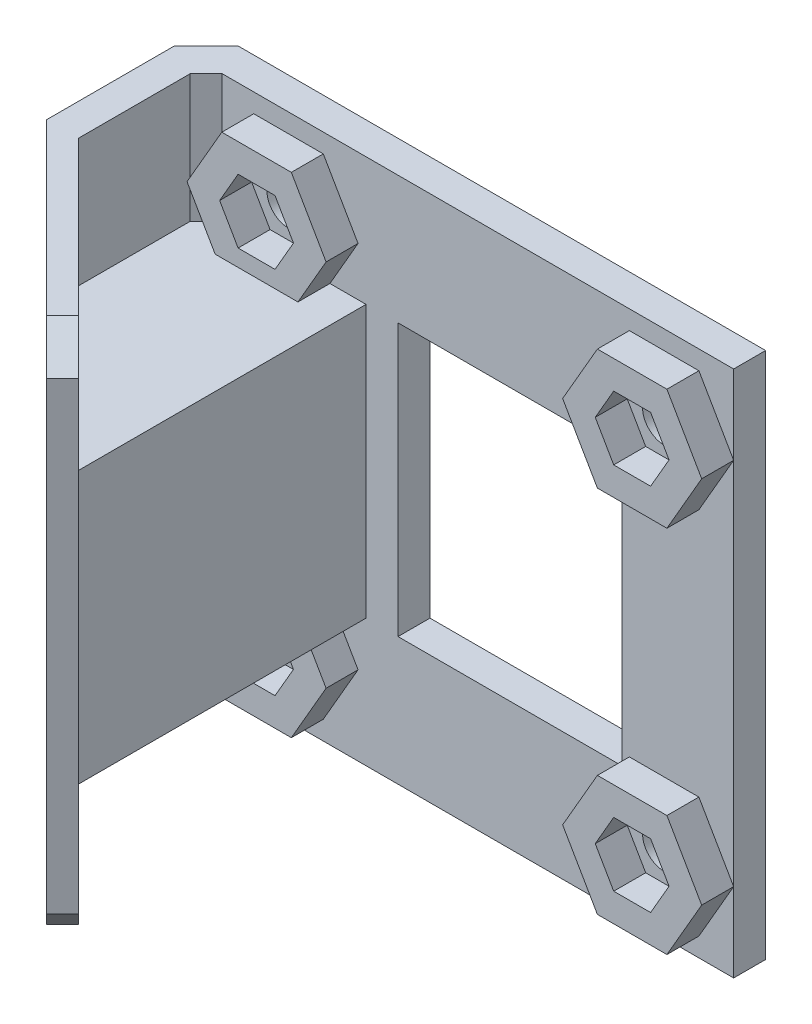
SolidWorks part; units mm, degrees
ref_plane "Front Plane" through (0, 0, 0) normal (0, 0, 1) x (1, 0, 0)
ref_plane "Top Plane" through (0, 0, 0) normal (0, 1, 0) x (1, 0, 0)
ref_plane "Right Plane" through (0, 0, 0) normal (1, 0, 0) x (0, 0, -1)
sketch "Sketch1" plane through (0, 0, 0) normal (0, 0, 1) x (1, 0, 0)
  line L1 (16.5, -16.5) -> (-16.5, -16.5)
  line L2 (16.5, -16.5) -> (16.5, 16.5)
  line L3 (16.5, 16.5) -> (-16.5, 16.5)
  line L4 (-16.5, -16.5) -> (-16.5, 16.5)
  line L5 (16.5, -16.5) -> (-16.5, 16.5) construction
  line L6 (16.5, 16.5) -> (-16.5, -16.5) construction
  circle A0 centre (-11.35, 11.55) radius 1.35
  circle A1 centre (12.15, 11.55) radius 1.35
  circle A2 centre (-11.35, -11.55) radius 1.35
  circle A3 centre (12.15, -11.55) radius 1.35
  point P0 (0, 0)
  point P9 (0, 0)
  dimension "D4" = 2.7
  dimension "D5" = 23.1
  dimension "D6" = 23.1
  dimension "D7" = 4.95
  dimension "D8" = 4.95
  dimension "D10" = 23.5
  dimension "D11" = 5.15
  dimension "D12" = 5.15
  dimension "D1" = 33
  dimension "D2" = 33
  dimension "D3" = 23.5
extrude "Boss-Extrude1" add sketch "Sketch1" along normal blind 2
sketch "Sketch4" plane through (-16.5, 0, 0) normal (-1, 0, 0) x (0, 0, 1)
  line L0 (2, -16.5) -> (0, -16.5) construction
  line L1 (0, 16.5) -> (10, 16.5)
  line L2 (0, 16.5) -> (0, -16.5)
  line L3 (0, -16.5) -> (10, -16.5)
  line L4 (10, 16.5) -> (10, -16.5)
  dimension "D1" = 10
extrude "Boss-Extrude3" add sketch "Sketch4" along normal blind 2
sketch "Sketch5" plane through (0, -16.5, 0) normal (0, -1, 0) x (1, 0, 0)
  line L0 (-18.5, 10) -> (-6.4792, 22.0208)
  line L1 (-6.4792, 22.0208) -> (-5.4792, 21.0208)
  line L2 (-5.4792, 21.0208) -> (-16.5, 10)
  line L3 (-16.5, 2) -> (-16.5, 10) construction
  line L4 (-16.5, 10) -> (-18.5, 10)
  dimension "D1" = 135
  dimension "D2" = 17
extrude "Boss-Extrude4" add sketch "Sketch5" against normal up to surface (33 mm away) up to face at (-6.1667, 16.5, 4)
sketch "Sketch6" plane through (-13.25, 0, 13.25) normal (0.7071, 0, -0.7071) x (-0.7071, 0, -0.7071)
  line L0 (-10.9896, 16.5) -> (-10.9896, -16.5) construction
  line L1 (-10.9896, 16.5) -> (4.5962, 16.5) construction
  line L2 (4.5962, -16.5) -> (-10.9896, -16.5) construction
  circle A0 centre (-5.9896, 13.5) radius 1.65
  circle A1 centre (-5.9896, -13.5) radius 1.65
  dimension "D1" = 3.3
  dimension "D2" = 5
  dimension "D3" = 3
  dimension "D4" = 5
  dimension "D5" = 3
  dimension "D6" = 3.3
extrude "Cut-Extrude1" cut sketch "Sketch6" against normal blind 2
chamfer "Chamfer1" distance 1 angle 45 1 edges at (-16.5, 0, 2)
sketch "Sketch7" plane through (0, 0, 2) normal (0, 0, 1) x (1, 0, 0)
  line L1 (-15.5, -7.5) -> (-7.5, -7.5)
  line L2 (-15.5, -7.5) -> (-15.5, 7.5)
  line L3 (-15.5, 7.5) -> (-7.5, 7.5)
  line L4 (-7.5, -7.5) -> (-7.5, 7.5)
  line L5 (-15.5, -7.5) -> (-7.5, 7.5) construction
  line L6 (-15.5, 7.5) -> (-7.5, -7.5) construction
  line L12 (0, 0) -> (-17.9167, 0) construction
  line L15 (-18.5, 16.5) -> (-18.5, -16.5) construction
  point P0 (-11.5, 0)
  point P5 (-11.5, 0)
  dimension "D1" = 3
  dimension "D2" = 15
  dimension "D4" = 8
extrude "Cut-Extrude3" cut sketch "Sketch7" against normal up to surface (2 mm away) and the other way up to surface up to face at (13.5, -11.55, 0) other way up to face at (-8.848, 13.5, 19.652)
sketch "Sketch9" plane through (0, 0, 0) normal (0, 0, -1) x (-1, 0, 0)
  line L1 (6.5, -8.5) -> (18.5, -8.5)
  line L2 (6.5, -8.5) -> (6.5, 8.5)
  line L3 (6.5, 8.5) -> (18.5, 8.5)
  line L4 (18.5, -8.5) -> (18.5, 8.5)
  line L8 (7.5, -7.5) -> (15.5, -7.5) construction
  line L9 (15.5, 7.5) -> (7.5, 7.5) construction
  line L10 (7.5, 7.5) -> (7.5, -7.5) construction
  line L11 (7.5, -7.5) -> (15.5, -7.5)
  line L12 (7.5, -7.5) -> (7.5, 7.5)
  line L13 (7.5, 7.5) -> (15.5, 7.5)
  line L14 (15.5, -7.5) -> (15.5, 7.5)
  line L15 (7.5, -7.5) -> (15.5, 7.5) construction
  line L16 (7.5, 7.5) -> (15.5, -7.5) construction
  line L17 (18.5, 16.5) -> (18.5, -16.5) construction
  point P0 (12.425, 0)
  point P13 (11.5, 0)
  point P19 (0, 0)
  dimension "D1" = 1
  dimension "D3" = 1
  dimension "D4" = 1
extrude "Boss-Extrude6" add sketch "Sketch9" against normal up to surface (22 mm away)
sketch "Sketch10" plane through (0, 0, 0) normal (0, 0, -1) x (-1, 0, 0)
  line L0 (-16.5, -16.5) -> (-16.5, 16.5) construction
  line L1 (-9.5, -8.5) -> (4.5, -8.5)
  line L2 (-9.5, -8.5) -> (-9.5, 8.5)
  line L3 (-9.5, 8.5) -> (4.5, 8.5)
  line L4 (4.5, -8.5) -> (4.5, 8.5)
  line L5 (-9.5, -8.5) -> (4.5, 8.5) construction
  line L6 (-9.5, 8.5) -> (4.5, -8.5) construction
  line L7 (7.5, 7.5) -> (7.5, -7.5) construction
  line L8 (-16.5, 16.5) -> (18.5, 16.5) construction
  line L9 (-16.5, -16.5) -> (18.5, -16.5) construction
  point P0 (-2.5, 0)
  dimension "D1" = 7
  dimension "D2" = 3
  dimension "D3" = 8
  dimension "D4" = 8
extrude "Cut-Extrude4" cut sketch "Sketch10" against normal up to surface (2 mm away) contours L2 L1 L4 L3 up to face at (-5.25, 0, 2)
sketch "Sketch12" plane through (0, 0, 2) normal (0, 0, 1) x (1, 0, 0)
  line L0 (16.5, -16.5) -> (16.5, 16.5) construction
  line L1 (14.4594, 11.55) -> (13.3047, 13.55)
  line L2 (13.3047, 13.55) -> (10.9953, 13.55)
  line L3 (10.9953, 13.55) -> (9.8406, 11.55)
  line L4 (9.8406, 11.55) -> (10.9953, 9.55)
  line L5 (10.9953, 9.55) -> (13.3047, 9.55)
  line L6 (13.3047, 9.55) -> (14.4594, 11.55)
  line L7 (14.4594, -11.55) -> (13.3047, -9.55)
  line L8 (13.3047, -9.55) -> (10.9953, -9.55)
  line L9 (10.9953, -9.55) -> (9.8406, -11.55)
  line L10 (9.8406, -11.55) -> (10.9953, -13.55)
  line L11 (10.9953, -13.55) -> (13.3047, -13.55)
  line L12 (13.3047, -13.55) -> (14.4594, -11.55)
  line L13 (-9.0406, 11.55) -> (-10.1953, 13.55)
  line L14 (-10.1953, 13.55) -> (-12.5047, 13.55)
  line L15 (-12.5047, 13.55) -> (-13.6594, 11.55)
  line L16 (-13.6594, 11.55) -> (-12.5047, 9.55)
  line L17 (-12.5047, 9.55) -> (-10.1953, 9.55)
  line L18 (-10.1953, 9.55) -> (-9.0406, 11.55)
  line L19 (-9.0406, -11.55) -> (-10.1953, -9.55)
  line L20 (-10.1953, -9.55) -> (-12.5047, -9.55)
  line L21 (-12.5047, -9.55) -> (-13.6594, -11.55)
  line L22 (-13.6594, -11.55) -> (-12.5047, -13.55)
  line L23 (-12.5047, -13.55) -> (-10.1953, -13.55)
  line L24 (-10.1953, -13.55) -> (-9.0406, -11.55)
  line L27 (16.5, 16.5) -> (-15.5, 16.5) construction
  line L29 (9.975, 15.3172) -> (7.8, 11.55)
  line L30 (7.8, 11.55) -> (9.975, 7.7828)
  line L31 (9.975, 7.7828) -> (14.325, 7.7828)
  line L32 (14.325, 7.7828) -> (16.5, 11.55)
  line L33 (16.5, 11.55) -> (14.325, 15.3172)
  line L34 (14.325, 15.3172) -> (9.975, 15.3172)
  line L35 (9.975, -7.7828) -> (7.8, -11.55)
  line L36 (7.8, -11.55) -> (9.975, -15.3172)
  line L37 (9.975, -15.3172) -> (14.325, -15.3172)
  line L38 (14.325, -15.3172) -> (16.5, -11.55)
  line L39 (16.5, -11.55) -> (14.325, -7.7828)
  line L40 (14.325, -7.7828) -> (9.975, -7.7828)
  line L41 (-9.175, -7.7828) -> (-13.525, -7.7828)
  line L42 (-13.525, -7.7828) -> (-15.7, -11.55)
  line L43 (-15.7, -11.55) -> (-13.525, -15.3172)
  line L44 (-13.525, -15.3172) -> (-9.175, -15.3172)
  line L45 (-9.175, -15.3172) -> (-7, -11.55)
  line L46 (-7, -11.55) -> (-9.175, -7.7828)
  line L47 (-9.175, 15.3172) -> (-13.525, 15.3172)
  line L48 (-13.525, 15.3172) -> (-15.7, 11.55)
  line L49 (-15.7, 11.55) -> (-13.525, 7.7828)
  line L50 (-13.525, 7.7828) -> (-9.175, 7.7828)
  line L51 (-9.175, 7.7828) -> (-7, 11.55)
  line L52 (-7, 11.55) -> (-9.175, 15.3172)
  circle A0 centre (12.15, 11.55) radius 2 construction
  circle A1 centre (12.15, -11.55) radius 2 construction
  circle A2 centre (-11.35, 11.55) radius 2 construction
  circle A3 centre (-11.35, -11.55) radius 2 construction
  circle A4 centre (12.15, 11.55) radius 3.7672 construction
  circle A5 centre (12.15, -11.55) radius 3.7672 construction
  circle A6 centre (-11.35, -11.55) radius 3.7672 construction
  circle A7 centre (-11.35, 11.55) radius 3.7672 construction
  point P38 (0, 0)
  point P69 (0, 0)
  dimension "D1" = 4
extrude "Boss-Extrude8" add sketch "Sketch12" along normal blind 2
chamfer "Chamfer3" distance 2 angle 45 1 edges at (-18.5, 0, 0)
chamfer "Chamfer4" distance 2 angle 45 2 edges at (-5.9792, -16.5, 21.5208) (-5.9792, 16.5, 21.5208)
